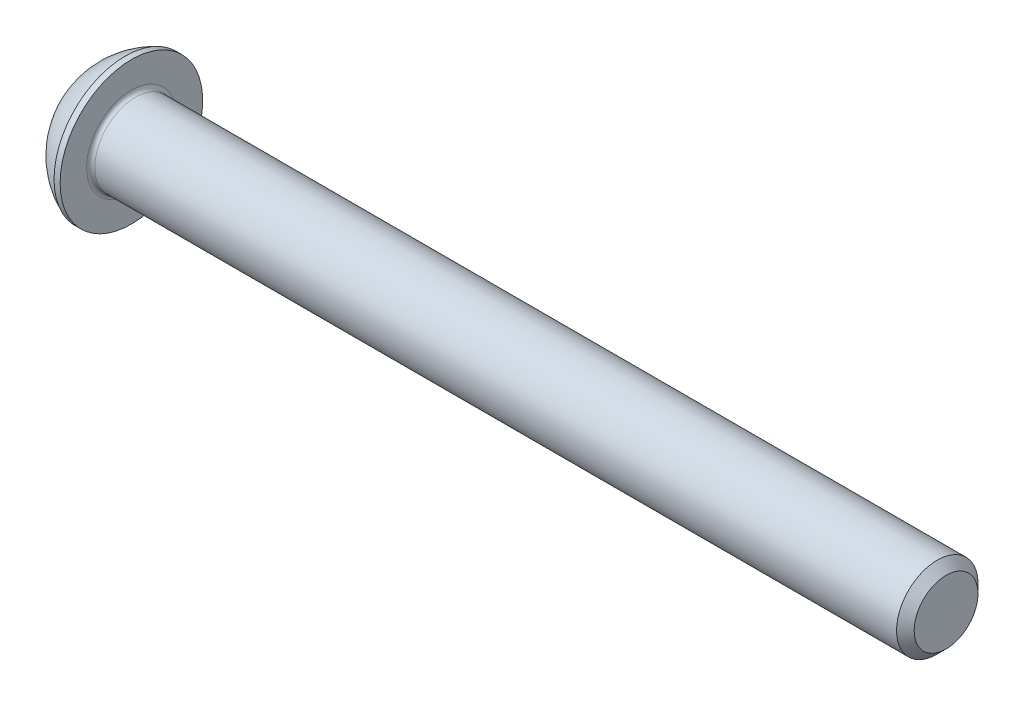
SolidWorks part; units mm, degrees
ref_plane "Plane1" through (0, 0, 0) normal (0, 0, 1) x (1, 0, 0)
ref_plane "Plane2" through (0, 0, 0) normal (0, 1, 0) x (1, 0, 0)
ref_plane "Plane3" through (0, 0, 0) normal (1, 0, 0) x (0, 0, -1)
sketch "BodySke" plane through (0, 0, 0) normal (0, 0, 1) x (1, 0, 0)
  line L0 (21.1, 0) -> (21.1, 0.7835)
  line L1 (20.8835, 1) -> (1.1, 1)
  line L2 (1.1, 1) -> (1.1, 1.75)
  line L3 (1.1, 1.75) -> (0.95, 1.75)
  line L4 (0, 0) -> (101.6, 0) construction
  line L5 (1.1, -1.75) -> (0.95, -1.75) construction
  line L6 (55.6768, -1) -> (1.1, -1) construction
  line L7 (21.1, 0) -> (0, 0)
  line L8 (0, 0.875) -> (0, -0.875) construction
  line L9 (0, 0) -> (0, 0.875)
  line L10 (21.1, 0.7835) -> (20.8835, 1)
  line L11 (21.1, -0.7835) -> (20.8835, -1) construction
  line L12 (1.5, 9.525) -> (1.5, -1) construction
  line L13 (1.1, 9.525) -> (1.1, -1) construction
  arc A1 (0, 0.875) -> (0.95, 1.75) centre (1.6839, 0) cw
  dimension "Diameter" = 2
  dimension "Length" = 20
  dimension "Head_dia" = 3.5
  dimension "D1" = 1.75
  dimension "Head_ht" = 1.1
  dimension "Head_side_ht" = 0.15
  dimension "Minor_dia" = 1.567
  dimension "Body_ch_ang" = 45
  dimension "Advance" = 0.4
  dimension "Thread_nom" = 20
revolve "BaseBody" add sketch "BodySke" angle 360 about L4
cosmetic thread "ThreadCosmetic" [suppressed] parameters "Thread_length"=19.2, "Thread_minor"=1.567
fillet "Fillet1" radius 0.1 1 edges at (1.1, 0, 1)
sketch "Sketch2" plane through (0, 0, 0) normal (0, 0, 1) x (1, 0, 0)
  line L0 (0, 0.715) -> (0.6, 0.715)
  line L1 (0.6, 0.715) -> (1.0128, 0)
  line L3 (1.0128, 0) -> (0, 0)
  line L4 (0, 0) -> (0, 0.715)
  line L5 (0, -0.715) -> (0.6, -0.715) construction
  line L6 (0, 0) -> (47.625, 0) construction
  dimension "D2" = 60
  dimension "PreBroach_depth" = 0.6
  dimension "PreBroach_dia" = 1.43
revolve "PreBroach" cut sketch "Sketch2" angle 360 about L6
sketch "Sketch3" plane through (0, 0, 0) normal (1, 0, 0) x (0, 0, -1)
  line L0 (-0.65, -0.3753) -> (-0.65, 0.3753)
  line L1 (-0.65, 0.3753) -> (0, 0.7506)
  line L2 (0, 0.7506) -> (0.65, 0.3753)
  line L3 (0.65, 0.3753) -> (0.65, -0.3753)
  line L4 (0.65, -0.3753) -> (0, -0.7506)
  line L5 (0, -0.7506) -> (-0.65, -0.3753)
  dimension "Hex_size" = 1.3
  dimension "D3" = 1.3
  dimension "D1" = 0.65
  dimension "D2" = 0.65
extrude "Hex" cut sketch "Sketch3" along normal blind 0.6
sketch "ThdSchSke" plane through (0, 0, 0) normal (0, 0, 1) x (1, 0, 0)
  line L0 (1.9, -0.7835) -> (1.7484, -1)
  line L1 (1.9, -0.7835) -> (2.0516, -1)
  line L2 (2.0516, -1) -> (2.0516, -1.25)
  line L3 (-3.175, 0) -> (5.1513, 0) construction
  line L5 (2.0516, -1.25) -> (1.7484, -1.25)
  line L6 (1.7484, -1.25) -> (1.7484, -1)
  dimension "Diameter" = 2
  dimension "Thread_minor" = 1.567
  dimension "SideAngle" = 55
  dimension "VeeAngle" = 70
  dimension "Overcut" = 2.5
  dimension "Start" = 1.9
revolve "ThreadSchematic" [suppressed] cut sketch "ThdSchSke" angle 360 about L3
pattern_linear "ThdSchPat" [suppressed]
equation "\"D1@BodySke\" = \"Head_dia@BodySke\" * .5"
equation "\"Thread_minor@ThreadCosmetic\" = \"Minor_dia@BodySke\""
equation "\"D1@Sketch3\" = \"Hex_size@Sketch3\" / 2"
equation "\"D2@Sketch3\" = \"D1@Sketch3\""
equation "\"D3@Sketch3\" = \"Hex_size@Sketch3\""
equation "\"Thread_length@ThreadCosmetic\" = ((sgn( (\"Length@BodySke\" - \"Advance@BodySke\" * 2.0) - \"Thread_nom@BodySke\" )-1)*( (\"Length@BodySke\" - \"Advance@BodySke\" * 2.0) - \"Thread_nom@BodySke\" ))/-2+ \"Thread_nom@BodySke\""
equation "\"Thread_minor@ThdSchSke\" = \"Minor_dia@BodySke\""
equation "\"Diameter@ThdSchSke\" = \"Diameter@BodySke\""
equation "\"Overcut@ThdSchSke\" = \"Diameter@BodySke\" * 1.25"
equation "\"Start@ThdSchSke\" = \"Head_ht@BodySke\" + \"Length@BodySke\" - \"Thread_length@ThreadCosmetic\"  '---Non-countersunk---"
equation "\"Num_threads@ThdSchPat\" = int( \"Thread_length@ThreadCosmetic\" / \"Advance@BodySke\" + 0.999 )  + 1"
equation "\"Advance@ThdSchPat\" = \"Thread_length@ThreadCosmetic\" /  (\"Num_threads@ThdSchPat\" - 1) 'relax it"
equation "\"Num_threads@ThdSchPat\" = \"Num_threads@ThdSchPat\" - sgn( \"Num_threads@ThdSchPat\" - 1) '---chamfered tips only---"
